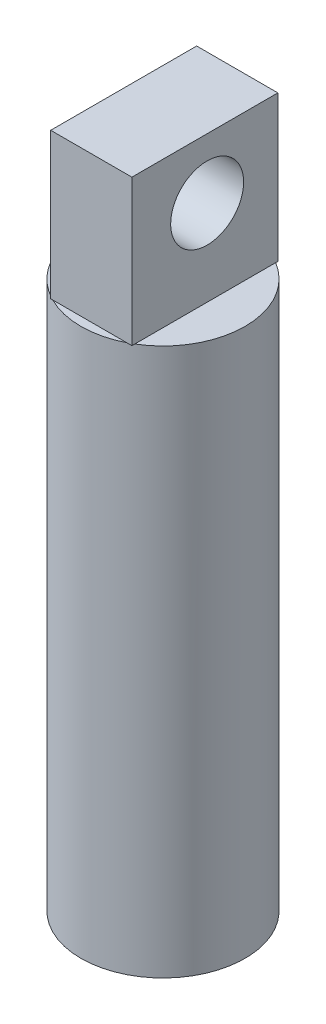
SolidWorks part; units mm, degrees
material "PF"
ref_plane "Plan de face" through (0, 0, 0) normal (0, 0, 1) x (1, 0, 0)
ref_plane "Plan de dessus" through (0, 0, 0) normal (0, 1, 0) x (1, 0, 0)
ref_plane "Plan de droite" through (0, 0, 0) normal (1, 0, 0) x (0, 0, -1)
sketch "Esquisse1" plane through (0, 0, 0) normal (0, 0, 1) x (1, 0, 0)
  line L1 (-2.1374, 2.6997) -> (2.3126, 2.6997)
  line L2 (-2.1374, 2.6997) -> (-2.1374, -5.3003)
  line L3 (-2.1374, -5.3003) -> (2.3126, -5.3003)
  line L4 (2.3126, 2.6997) -> (2.3126, -5.3003)
  dimension "D1" = 4.45
  dimension "D2" = 8
extrude "Boss.-Extru.1" add sketch "Esquisse1" along normal blind 8
sketch "Esquisse2" plane through (0, -5.3003, 0) normal (0, -1, 0) x (1, 0, 0)
  circle A0 centre (0, 3.9834) radius 4.5
  dimension "D1" = 9
extrude "Boss.-Extru.2" add sketch "Esquisse2" along normal blind 30
sketch "Esquisse4" plane through (2.3126, 0, 0) normal (1, 0, 0) x (0, 0, -1)
  circle A0 centre (-3.8757, -0.5893) radius 2
extrude "Enlèv. mat.-Extru.1" cut sketch "Esquisse4" against normal blind 18
